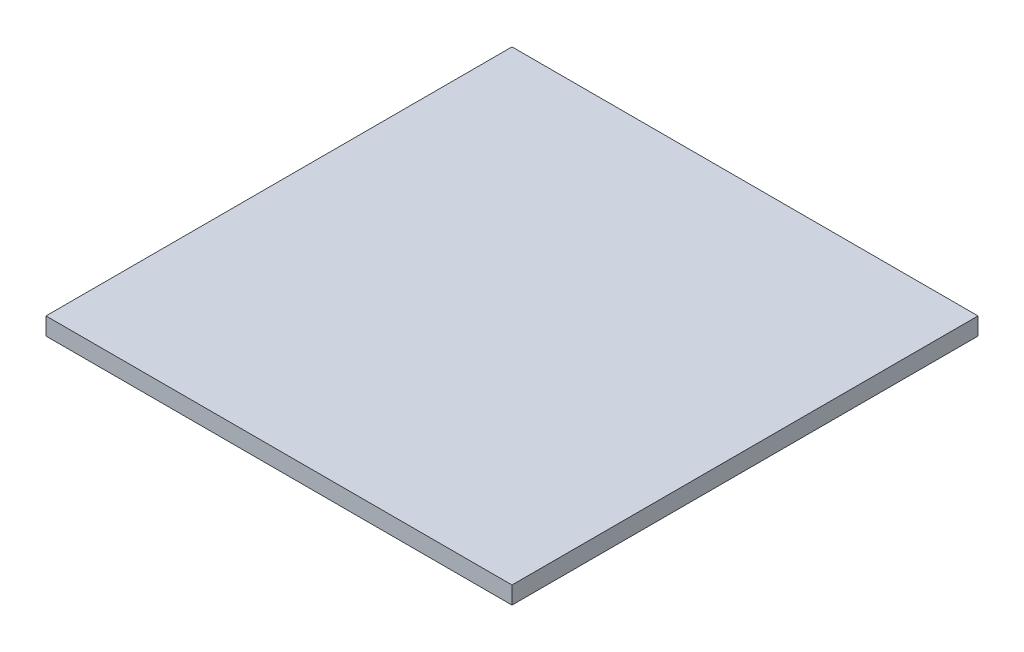
SolidWorks part; units mm, degrees
ref_plane "Front Plane" through (0, 0, 0) normal (0, 0, 1) x (1, 0, 0)
ref_plane "Top Plane" through (0, 0, 0) normal (0, 1, 0) x (1, 0, 0)
ref_plane "Right Plane" through (0, 0, 0) normal (1, 0, 0) x (0, 0, -1)
sketch "Sketch1" plane through (0, 0, 0) normal (0, 1, 0) x (1, 0, 0)
  line L1 (-20, 20) -> (20, 20)
  line L2 (-20, 20) -> (-20, -20)
  line L3 (-20, -20) -> (20, -20)
  line L4 (20, 20) -> (20, -20)
  line L5 (-20, 20) -> (20, -20) construction
  line L6 (-20, -20) -> (20, 20) construction
  point P0 (0, 0)
  dimension "D1" = 40
  dimension "D2" = 40
extrude "Boss-Extrude1" add sketch "Sketch1" along normal blind 1.5
equation "\"D2@Sketch1\"=\"D1@Sketch1\""
